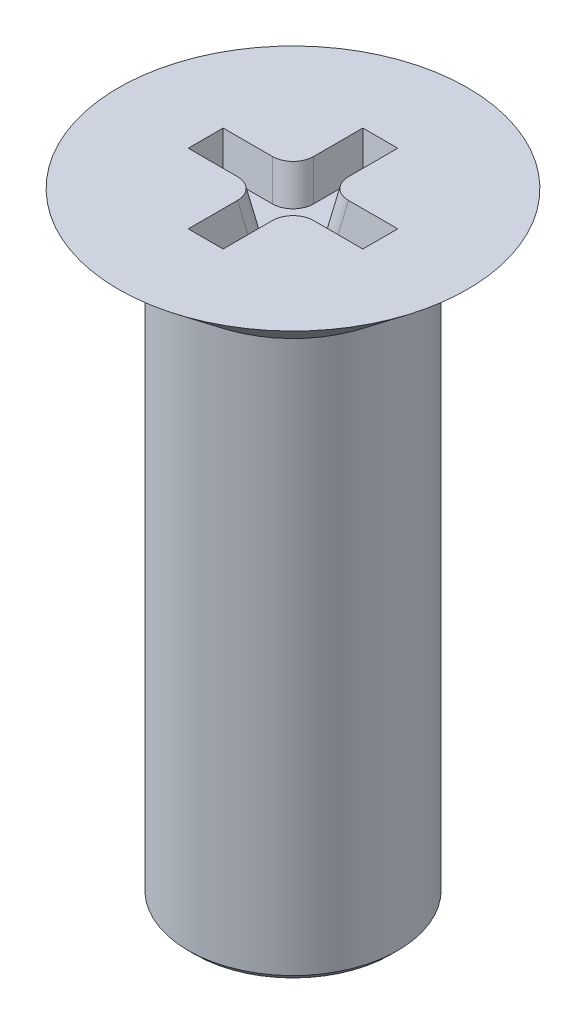
SolidWorks part; units mm, degrees
material "AISI 321 退火不锈钢 (SS)"
ref_plane "前视基准面" through (0, 0, 0) normal (0, 0, 1) x (1, 0, 0)
ref_plane "上视基准面" through (0, 0, 0) normal (0, 1, 0) x (1, 0, 0)
ref_plane "右视基准面" through (0, 0, 0) normal (1, 0, 0) x (0, 0, -1)
other "Configuration Table"
sketch "草图1" plane through (0, 0, 0) normal (0, 0, 1) x (1, 0, 0)
  line L0 (0, 0) -> (2.5, 0)
  line L1 (2.5, 0) -> (1.5, -0.8)
  line L2 (1.5, -0.8) -> (0, -0.8)
  line L3 (0, -0.8) -> (0, 0)
  dimension "D1" = 2.5
  dimension "D2" = 0.8
  dimension "D3" = 1.5
revolve "旋转1" add sketch "草图1" angle 360 about L3
sketch "草图2" plane through (0, -0.8, 0) normal (0, -1, 0) x (1, 0, 0)
  circle A1 centre (0, 0) radius 1.5
  circle A2 centre (0, 0) radius 1.5
  dimension "D1" = 0
extrude "凸台-拉伸1" add sketch "草图2" along normal blind 8
cosmetic thread "装饰螺纹线1" parameters "D2"=2.459
chamfer "倒角1" distance 0.1 angle 45 1 edges at (0, -8.8, -1.5)
sketch "草图3" plane through (0, 0, 0) normal (0, 1, 0) x (1, 0, 0)
  line L1 (-1.25, -0.25) -> (1.25, -0.25)
  line L2 (-1.25, -0.25) -> (-1.25, 0.25)
  line L3 (-1.25, 0.25) -> (1.25, 0.25)
  line L4 (1.25, -0.25) -> (1.25, 0.25)
  line L5 (-1.25, -0.25) -> (1.25, 0.25) construction
  line L6 (-1.25, 0.25) -> (1.25, -0.25) construction
  line L7 (-0.25, 1.25) -> (0.25, 1.25)
  line L8 (-0.25, 1.25) -> (-0.25, -1.25)
  line L9 (-0.25, -1.25) -> (0.25, -1.25)
  line L10 (0.25, 1.25) -> (0.25, -1.25)
  line L11 (-0.25, 1.25) -> (0.25, -1.25) construction
  line L12 (-0.25, -1.25) -> (0.25, 1.25) construction
  point P0 (0, 0)
  point P6 (0, 0)
  dimension "D1" = 0.5
  dimension "D2" = 0.5
  dimension "D3" = 2.5
  dimension "D4" = 2.5
extrude "切除-拉伸1" cut sketch "草图3" against normal blind 0.5 draft 10 contours L3 L10 L1 L4 | L10 L7 L8 L3 | L8 L3 L2 L1 | L10 L3 L8 L1 | L10 L1 L8 L9
fillet "圆角1" radius 0.3 4 edges at (-0.2059, -0.25, -0.2059) (0.2059, -0.25, -0.2059) (-0.2059, -0.25, 0.2059) (0.2059, -0.25, 0.2059)
